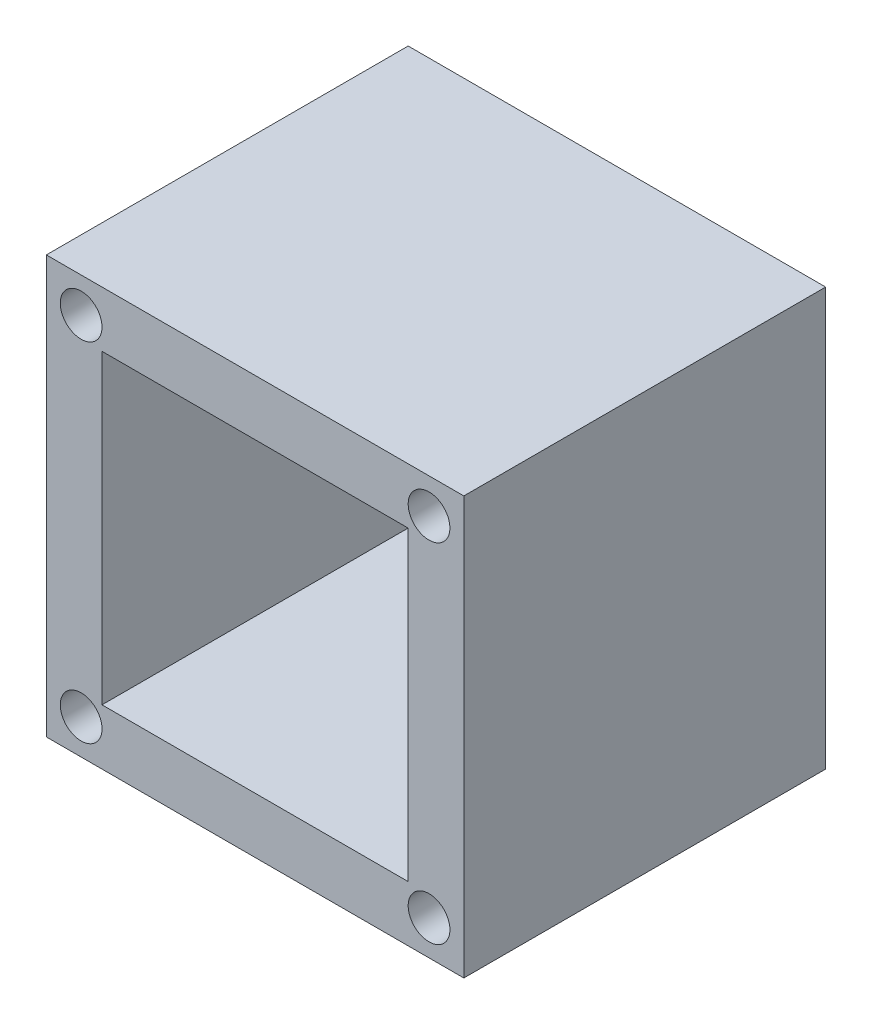
SolidWorks part; units mm, degrees
ref_plane "Plan de face" through (0, 0, 0) normal (0, 0, 1) x (1, 0, 0)
ref_plane "Plan de dessus" through (0, 0, 0) normal (0, 1, 0) x (1, 0, 0)
ref_plane "Plan de droite" through (0, 0, 0) normal (1, 0, 0) x (0, 0, -1)
sketch "Croquis1" plane through (0, 0, 0) normal (0, 0, 1) x (1, 0, 0)
  line L0 (-1.75, 4.25) -> (1.75, 4.25)
  line L1 (-15, 15) -> (15, 15)
  line L2 (-15, 15) -> (-15, -15)
  line L3 (-15, -15) -> (15, -15)
  line L4 (15, 15) -> (15, -15)
  line L5 (1.75, -4.25) -> (-1.75, -4.25)
  arc A0 (-1.75, 4.25) -> (-1.75, -4.25) centre (-1.75, 0) ccw
  arc A1 (1.75, -4.25) -> (1.75, 4.25) centre (1.75, 0) ccw
  circle A2 centre (-8, 0) radius 1
  circle A3 centre (8, 0) radius 1
  dimension "D1" = 2
  dimension "D2" = 4.25
  dimension "D4" = 4.25
  dimension "D5" = 2
  dimension "D3" = 3.5
  dimension "D6" = 30
  dimension "D7" = 30
extrude "Saliente-Extruir2" add sketch "Croquis1" against normal blind 1
sketch "Croquis2" plane through (0, 0, 0) normal (0, 0, 1) x (1, 0, 0)
  line L1 (-15, 15) -> (15, 15)
  line L2 (-15, 15) -> (-15, -15)
  line L3 (-15, -15) -> (15, -15)
  line L4 (15, 15) -> (15, -15)
  line L5 (-11, 11) -> (11, 11)
  line L6 (-11, 11) -> (-11, -11)
  line L7 (-11, -11) -> (11, -11)
  line L8 (11, 11) -> (11, -11)
  dimension "D1" = 4
  dimension "D2" = 4
  dimension "D3" = 4
  dimension "D4" = 4
extrude "Saliente-Extruir3" add sketch "Croquis2" along normal blind 30
sketch "Croquis4" plane through (0, 0, 30) normal (0, 0, 1) x (1, 0, 0)
  line L0 (15, 15) -> (-15, 15) construction
  line L1 (-15, 15) -> (-15, -15) construction
  line L2 (0, 15) -> (0, -15) construction
  line L3 (-15, -15) -> (15, -15) construction
  line L4 (-15, 0) -> (15, 0) construction
  line L5 (15, -15) -> (15, 15) construction
  circle A0 centre (-12.5, 12.5) radius 1.5
  circle A1 centre (12.5, 12.5) radius 1.5
  circle A2 centre (12.5, -12.5) radius 1.5
  circle A3 centre (-12.5, -12.5) radius 1.5
  dimension "D1" = 3
  dimension "D2" = 2.5
  dimension "D3" = 2.5
extrude "Cortar-Extruir2" cut sketch "Croquis4" against normal blind 44
sketch "Croquis6" plane through (-15, 0, 0) normal (-1, 0, 0) x (0, 0, 1)
  line L0 (-1, -15) -> (30, -15) construction
  line L1 (-1, 15) -> (4, 15)
  line L2 (-1, 15) -> (-1, -15)
  line L3 (-1, -15) -> (4, -15)
  line L4 (4, 15) -> (4, -15)
  dimension "D1" = 5
extrude "Cortar-Extruir4" cut sketch "Croquis6" against normal blind 46
